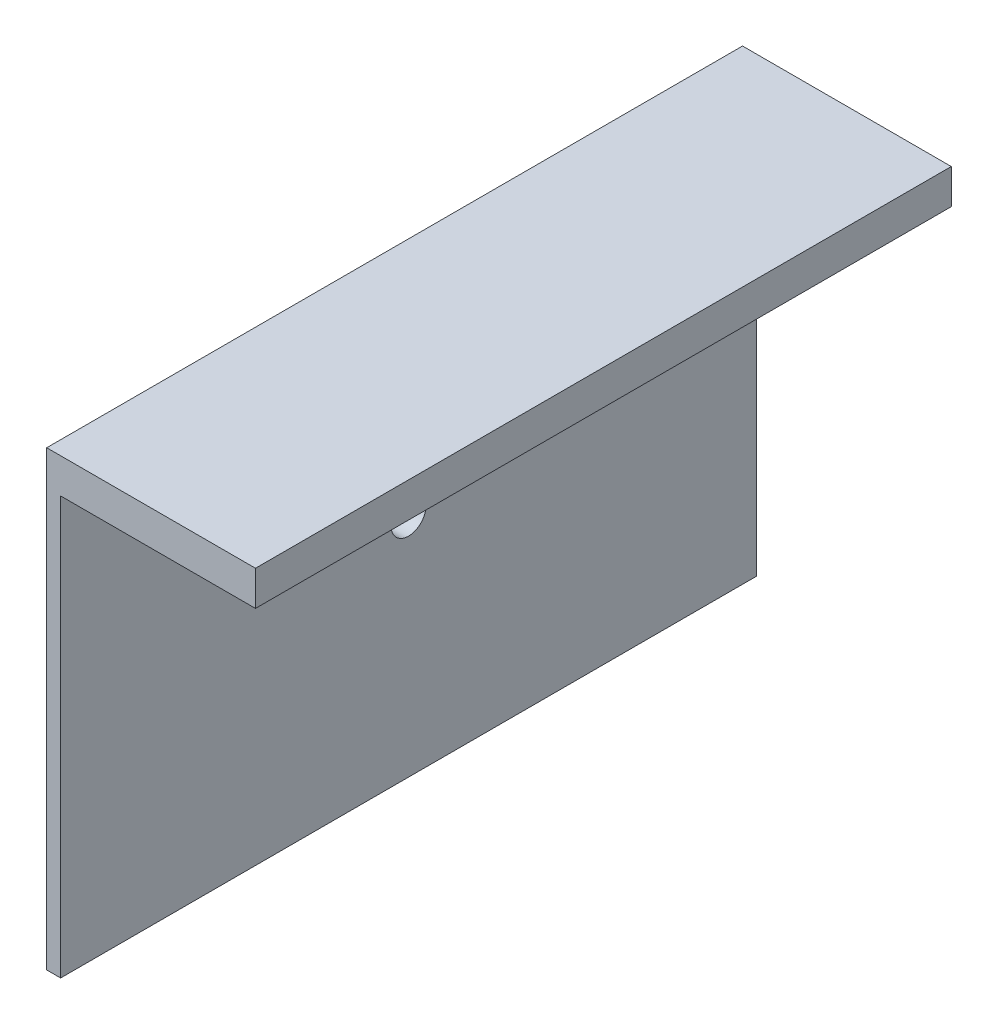
SolidWorks part; units mm, degrees
ref_plane "Front Plane" through (0, 0, 0) normal (0, 0, 1) x (1, 0, 0)
ref_plane "Top Plane" through (0, 0, 0) normal (0, 1, 0) x (1, 0, 0)
ref_plane "Right Plane" through (0, 0, 0) normal (1, 0, 0) x (0, 0, -1)
sketch "Sketch1" plane through (0, 0, 0) normal (1, 0, 0) x (0, 0, -1)
  line L1 (-50, -32.5) -> (50, -32.5)
  line L2 (-50, -32.5) -> (-50, 32.5)
  line L3 (-50, 32.5) -> (50, 32.5)
  line L4 (50, -32.5) -> (50, 32.5)
  line L5 (-50, -32.5) -> (50, 32.5) construction
  line L6 (-50, 32.5) -> (50, -32.5) construction
  circle A0 centre (0, 0) radius 2.5
  point P0 (0, 0)
  dimension "D3" = 5
  dimension "D1" = 100
  dimension "D2" = 65
extrude "Boss-Extrude1" add sketch "Sketch1" along normal blind 2
sketch "Sketch2" plane through (2, 0, 0) normal (1, 0, 0) x (0, 0, -1)
  line L0 (-50, 32.5) -> (-50, -32.5) construction
  line L1 (50, -32.5) -> (50, 32.5) construction
  line L2 (-50, 27.5) -> (50, 27.5)
  line L3 (50, 27.5) -> (50, 32.5)
  line L4 (50, 32.5) -> (-50, 32.5)
  line L5 (-50, 32.5) -> (-50, 27.5)
  point P0 (-50, 27.5)
  point P1 (50, 27.5)
  dimension "D1" = 5
  dimension "D2" = 5
extrude "Boss-Extrude2" add sketch "Sketch2" along normal blind 28
